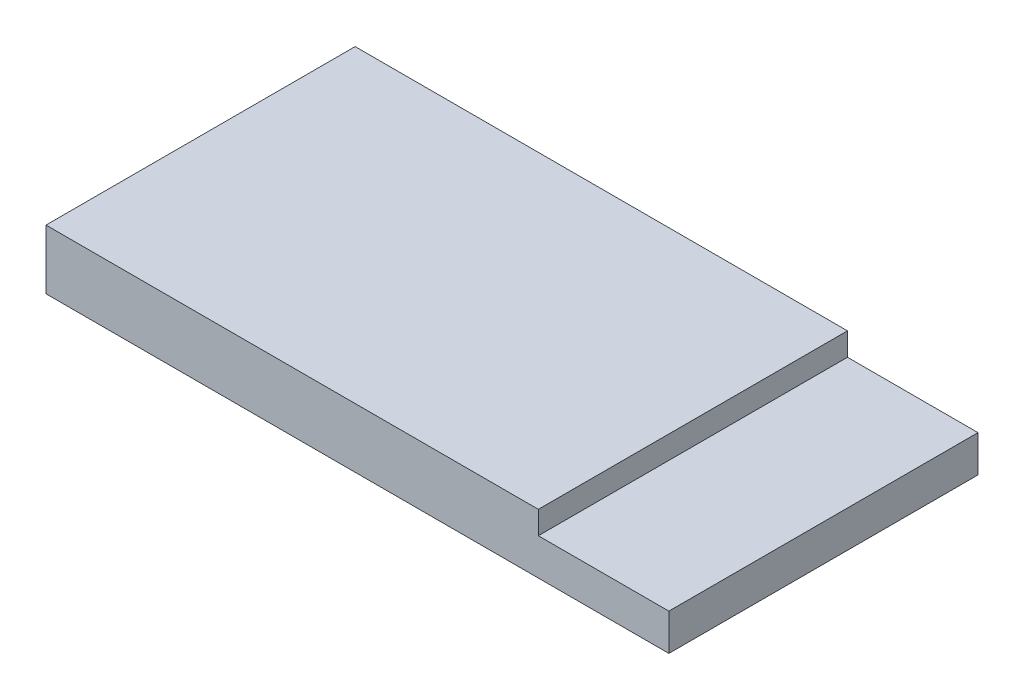
SolidWorks part; units mm, degrees
ref_plane "前视基准面" through (0, 0, 0) normal (0, 0, 1) x (1, 0, 0)
ref_plane "上视基准面" through (0, 0, 0) normal (0, 1, 0) x (1, 0, 0)
ref_plane "右视基准面" through (0, 0, 0) normal (1, 0, 0) x (0, 0, -1)
sketch "草图1" plane through (0, 0, 0) normal (0, 1, 0) x (1, 0, 0)
  line L0 (-42.149, 0) -> (47.6072, 0) construction
  line L1 (-13.6, 6.75) -> (13.6, 6.75)
  line L2 (-13.6, 6.75) -> (-13.6, -6.75)
  line L3 (-13.6, -6.75) -> (13.6, -6.75)
  line L4 (13.6, 6.75) -> (13.6, -6.75)
  line L5 (0, 33.3553) -> (0, -32.7489) construction
  dimension "D1" = 13.5
  dimension "D2" = 27.2
extrude "拉伸1" add sketch "草图1" along normal blind 1.6
sketch "草图2" plane through (0, 1.6, 0) normal (0, 1, 0) x (-1, 0, 0)
  line L0 (-13.6, -6.75) -> (13.6, -6.75) construction
  line L1 (13.6, 6.75) -> (-7.9, 6.75)
  line L2 (13.6, 6.75) -> (13.6, -6.75)
  line L3 (13.6, -6.75) -> (-7.9, -6.75)
  line L4 (-7.9, 6.75) -> (-7.9, -6.75)
  dimension "D1" = 21.5
extrude "拉伸2" add sketch "草图2" along normal blind 1
